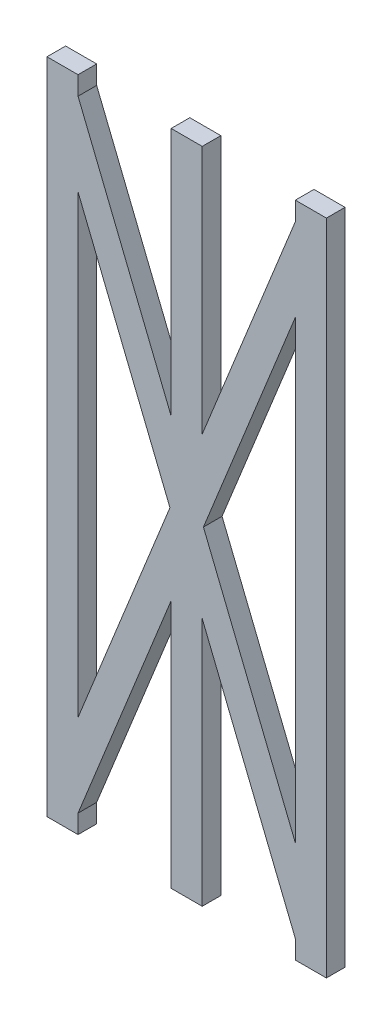
SolidWorks part; units mm, degrees
ref_plane "Alzado" through (0, 0, 0) normal (0, 0, 1) x (1, 0, 0)
ref_plane "Planta" through (0, 0, 0) normal (0, 1, 0) x (1, 0, 0)
ref_plane "Vista lateral" through (0, 0, 0) normal (1, 0, 0) x (0, 0, -1)
sketch "Sketch1" plane through (0, 0, 0) normal (0, 0, 1) x (1, 0, 0)
  line L0 (0, 0) -> (0, 106)
  line L1 (0, 106) -> (5, 106)
  line L2 (5, 106) -> (5, 0)
  line L3 (5, 0) -> (0, 0)
  line L4 (40, 106) -> (45, 106)
  line L5 (40, 0) -> (40, 106)
  line L6 (45, 106) -> (45, 0)
  line L7 (45, 0) -> (40, 0)
  line L8 (5, 103) -> (40, 16.3502)
  line L9 (5, 89.6498) -> (40, 3)
  line L10 (0, 53) -> (45, 53) construction
  line L11 (5, 16.3502) -> (40, 103)
  line L12 (5, 3) -> (40, 89.6498)
  line L14 (20, 106) -> (25, 106)
  line L15 (20, 106) -> (20, 0)
  line L16 (20, 0) -> (25, 0)
  line L17 (25, 106) -> (25, 0)
  line L18 (20, 106) -> (25, 0) construction
  line L19 (20, 0) -> (25, 106) construction
  point P19 (22.5, 53)
  point P20 (22.5, 53)
  dimension "D1" = 5
  dimension "D2" = 106
  dimension "D4" = 3
  dimension "D5" = 3
  dimension "D6" = 5
  dimension "D7" = 45
  dimension "D8" = 5
  dimension "D3" = 2
extrude "Boss-Extrude1" add sketch "Sketch1" along normal blind 3 contours L0 L10 L2 L1 | L9 L11 L8 L2 | L10 L0 L3 L2 | L2 L12 L9 L11 | L10 L9 L12 | L8 L12 L5 L11 | L5 L10 L6 L4 | L10 L5 L7 L6 | L12 L9 L5 L8 | L11 L10 L8 | L8 L15 L11 | L17 L14 L15 L8 L11 | L17 L9 L12 L15 L16 | L9 L15 L12 | L17 L12 L9 | L17 L11 L8
